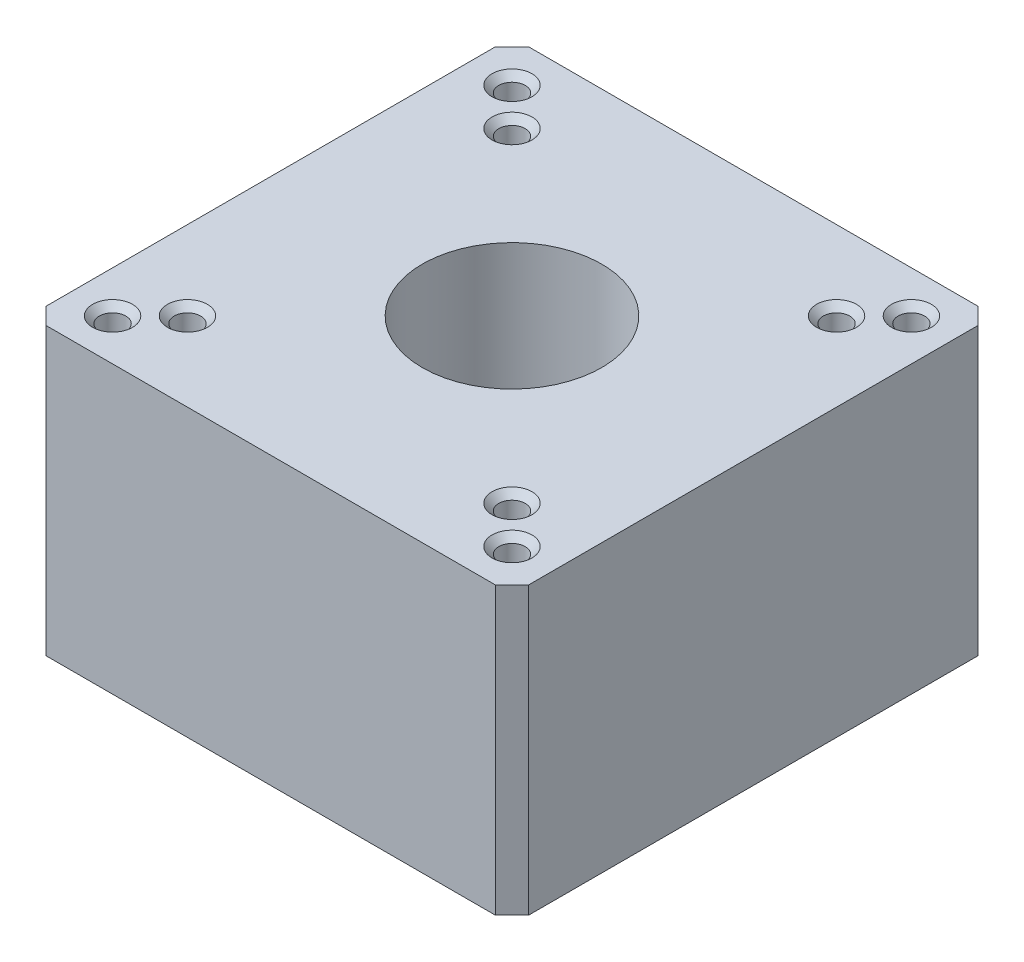
SolidWorks part; units mm, degrees
ref_plane "Front Plane" through (0, 0, 0) normal (0, 0, 1) x (1, 0, 0)
ref_plane "Top Plane" through (0, 0, 0) normal (0, 1, 0) x (1, 0, 0)
ref_plane "Right Plane" through (0, 0, 0) normal (1, 0, 0) x (0, 0, -1)
sketch "Sketch1" plane through (0, 0, 0) normal (0, 1, 0) x (1, 0, 0)
  line L1 (36.83, -36.83) -> (-36.83, -36.83)
  line L2 (36.83, -36.83) -> (36.83, 36.83)
  line L3 (36.83, 36.83) -> (-36.83, 36.83)
  line L4 (-36.83, -36.83) -> (-36.83, 36.83)
  line L5 (36.83, -36.83) -> (-36.83, 36.83) construction
  line L6 (36.83, 36.83) -> (-36.83, -36.83) construction
  circle A0 centre (0, 0) radius 13.6922
  point P0 (0, 0)
  dimension "D3" = 27.3844
  dimension "D1" = 73.66
  dimension "D2" = 73.66
extrude "Boss-Extrude1" add sketch "Sketch1" along normal blind 43.6562
chamfer "Chamfer2" distance 2.54 angle 45 4 edges at (36.83, 21.8281, -36.83) (-36.83, 21.8281, -36.83) (-36.83, 21.8281, 36.83) (36.83, 21.8281, 36.83)
sketch "Sketch2" plane through (0, 43.6562, 0) normal (0, 1, 0) x (1, 0, 0)
  line L0 (-55, 0) -> (55, 0) construction
  line L1 (0, -55) -> (0, 55) construction
  point P0 (30.48, 30.48)
  point P1 (-30.48, 30.48)
  point P4 (-30.48, -30.48)
  point P5 (30.48, -30.48)
  dimension "D1" = 60.96
  dimension "D2" = 60.96
  dimension "D3" = 30.48
hole_wizard "#10-32 Tapped Hole1" positions "Sketch2" profile "Sketch3" tap size "#10-32" standard "ANSI Inch" end condition up to next
sketch "Sketch3" plane through (30.48, 43.6562, -30.48) normal (1, 0, 0) x (0, 0, 1)
  line L0 (0, 0) -> (0, 43.6562)
  line L1 (0, 43.6562) -> (2.0193, 43.6562)
  line L2 (2.0193, 43.6562) -> (2.0193, 1.0287)
  line L3 (2.0193, 1.0287) -> (3.048, 0)
  line L5 (3.048, 0) -> (0, 0)
  line L6 (-2.0193, 1.0287) -> (-3.048, 0) construction
  line L11 (0, -6.35) -> (0, 107.95) construction
  dimension "Thru Tap Drill Dia." = 4.0386
  dimension "Thru Tap Drill Depth" = 43.6562
  dimension "Near C'Sink Dia." = 6.096
  dimension "Near C'Sink Angle" = 90
cosmetic thread "Hole Thread1" parameters "D2"=4.826
cosmetic thread "Hole Thread2" parameters "D2"=4.826
cosmetic thread "Hole Thread3" parameters "D2"=4.826
cosmetic thread "Hole Thread4" parameters "D2"=4.826
sketch "Sketch4" plane through (0, 43.6562, 0) normal (0, 1, 0) x (1, 0, 0)
  line L0 (-24.0109, 0) -> (24.0109, 0) construction
  line L1 (0, -24.0109) -> (0, 24.0109) construction
  point P0 (-24.765, 24.765)
  point P1 (24.765, 24.765)
  point P4 (-24.765, -24.765)
  point P5 (24.765, -24.765)
  dimension "D1" = 49.53
  dimension "D2" = 49.53
  dimension "D3" = 24.765
hole_wizard "#10-32 Tapped Hole2" positions "Sketch4" profile "Sketch5" tap size "#10-32" standard "ANSI Inch"
cosmetic thread "Hole Thread5" parameters "D1"=2.032, "D2"=4.826
cosmetic thread "Hole Thread6" parameters "D1"=2.032, "D2"=4.826
cosmetic thread "Hole Thread7" parameters "D1"=2.032, "D2"=4.826
cosmetic thread "Hole Thread8" parameters "D1"=2.032, "D2"=4.826
sketch "Sketch5" plane through (-24.765, 43.6562, -24.765) normal (1, 0, 0) x (0, 0, 1)
  line L0 (0, 0) -> (0, 23.0573)
  line L1 (0, 23.0573) -> (2.0193, 21.844)
  line L2 (2.0193, 21.844) -> (2.0193, 1.0287)
  line L3 (2.0193, 1.0287) -> (3.048, 0)
  line L5 (3.048, 0) -> (0, 0)
  line L6 (-2.0193, 1.0287) -> (-3.048, 0) construction
  line L10 (0, 23.0573) -> (-2.0193, 21.844) construction
  line L11 (0, -6.35) -> (0, 107.95) construction
  dimension "Tap Drill Dia." = 4.0386
  dimension "Tap Drill Depth" = 21.844
  dimension "Near C'Sink Dia." = 6.096
  dimension "Near C'Sink Angle" = 90
  dimension "Drill Angle" = 118
